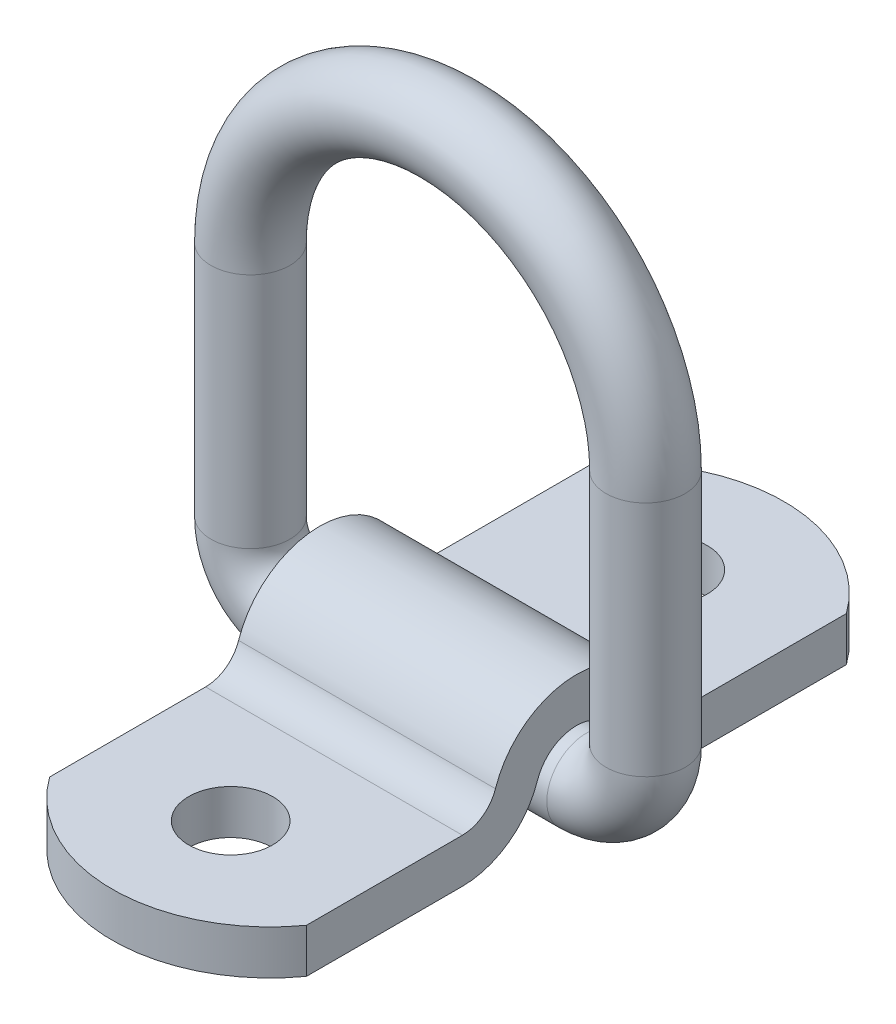
SolidWorks part; units mm, degrees
ref_plane "Front Plane" through (0, 0, 0) normal (0, 0, 1) x (1, 0, 0)
ref_plane "Top Plane" through (0, 0, 0) normal (0, 1, 0) x (1, 0, 0)
ref_plane "Right Plane" through (0, 0, 0) normal (1, 0, 0) x (0, 0, -1)
sketch "Sketch1" plane through (0, 0, 0) normal (0, 0, 1) x (1, 0, 0)
  line L1 (0, 0) -> (0, 42.8625) construction
  line L2 (-19.05, 23.8125) -> (-19.05, 4.7625) construction
  line L3 (-12.7, 23.8125) -> (-12.7, 3.175) construction
  line L4 (12.7, 23.8125) -> (12.7, 3.175) construction
  line L5 (19.05, 23.8125) -> (19.05, 4.7625) construction
  line L6 (12.7, 3.175) -> (-12.7, 3.175) construction
  line L7 (11.1125, -3.175) -> (-19.05, -3.175) construction
  line L8 (0, 3.175) -> (0, -3.175) construction
  line L10 (-15.875, 23.8125) -> (-15.875, 4.7625)
  line L11 (15.875, 23.8125) -> (15.875, 4.7625)
  line L12 (-11.1125, 0) -> (11.1125, 0)
  line L13 (-19.05, 4.7625) -> (-19.05, -3.175) construction
  arc A0 (19.05, 23.8125) -> (-19.05, 23.8125) centre (0, 23.8125) ccw construction
  arc A1 (12.7, 23.8125) -> (-12.7, 23.8125) centre (0, 23.8125) ccw construction
  circle A2 centre (0, 39.6875) radius 3.175 construction
  circle A3 centre (0, 0) radius 3.175 construction
  arc A4 (15.875, 23.8125) -> (-15.875, 23.8125) centre (0, 23.8125) ccw
  arc A5 (-11.1125, 0) -> (-15.875, 4.7625) centre (-11.1125, 4.7625) cw
  arc A6 (11.1125, 0) -> (15.875, 4.7625) centre (11.1125, 4.7625) ccw
  arc A7 (-11.1125, 3.175) -> (-12.7, 4.7625) centre (-11.1125, 4.7625) cw construction
  arc A8 (-11.1125, -3.175) -> (-19.05, 4.7625) centre (-11.1125, 4.7625) cw construction
  arc A9 (11.1125, -3.175) -> (19.05, 4.7625) centre (11.1125, 4.7625) ccw construction
  dimension "C" = 6.35
  dimension "D1" = 4.7625
  dimension "A" = 25.4
  dimension "B" = 46.0375
sketch "Sketch2" plane through (0, 0, 0) normal (1, 0, 0) x (0, 0, -1)
  circle A0 centre (0, 0) radius 3.175
sweep "Sweep1" add profiles "Sketch2" path "Sketch1"
sketch "Sketch3" plane through (0, 0, 0) normal (1, 0, 0) x (0, 0, -1)
  line L0 (-26.9875, -3.302) -> (26.9875, -3.302) construction
  line L1 (-26.9875, -3.302) -> (-26.9875, 0.254)
  line L2 (-26.9875, 0.254) -> (26.9875, 0.254) construction
  line L3 (0, 0) -> (0, -3.302) construction
  line L4 (26.9875, -3.302) -> (26.9875, 0.254)
  line L5 (-26.9875, -3.302) -> (-9.1581, -3.302)
  line L6 (-26.9875, 0.254) -> (-9.1581, 0.254)
  line L7 (-17.4625, -3.302) -> (-17.4625, 0.254) construction
  line L8 (26.9875, -3.302) -> (9.1581, -3.302)
  line L9 (26.9875, 0.254) -> (9.1581, 0.254)
  arc A0 (-9.1581, -3.302) -> (-3.133, 1.0427) centre (-9.1581, 3.048) ccw
  arc A1 (-3.133, 1.0427) -> (3.133, 1.0427) centre (0, 0) cw
  arc A2 (-9.1581, 0.254) -> (-6.5071, 2.1657) centre (-9.1581, 3.048) ccw
  arc A3 (-6.5071, 2.1657) -> (6.5071, 2.1657) centre (0, 0) cw
  arc A4 (9.1581, 0.254) -> (6.5071, 2.1657) centre (9.1581, 3.048) cw
  arc A5 (9.1581, -3.302) -> (3.133, 1.0427) centre (9.1581, 3.048) cw
  circle A6 centre (0, 0) radius 3.302 construction
  dimension "D1" = 34.925
  dimension "D4" = 6.604
  dimension "D5" = 6.35
  dimension "D2" = 3.556
  dimension "D3" = 53.975
extrude "Boss-Extrude1" add sketch "Sketch3" along normal mid plane 20.6375 separate body
sketch "Sketch4" plane through (0, -3.302, 0) normal (0, -1, 0) x (1, 0, 0)
  line L0 (-10.3187, 21.6911) -> (-10.3187, 26.9875)
  line L1 (-10.3187, 26.9875) -> (-10.3187, 27.2415)
  line L2 (-10.3187, 27.2415) -> (10.3187, 27.2415)
  line L3 (10.3187, 27.2415) -> (10.3187, 26.9875)
  line L4 (10.3187, 26.9875) -> (10.3187, 21.6911)
  line L5 (0, 14.2875) -> (0, 0) construction
  line L6 (10.3187, 26.9875) -> (-10.3187, 26.9875) construction
  line L7 (-10.3187, 0) -> (10.3188, 0) construction
  line L8 (10.3187, -26.9875) -> (10.3187, -21.6911)
  line L9 (10.3187, -27.2415) -> (10.3187, -26.9875)
  line L10 (-10.3187, -27.2415) -> (10.3187, -27.2415)
  line L11 (-10.3187, -26.9875) -> (-10.3187, -27.2415)
  line L12 (-10.3187, -21.6911) -> (-10.3187, -26.9875)
  arc A0 (10.3187, 21.6911) -> (-10.3187, 21.6911) centre (0, 14.2875) ccw
  circle A1 centre (0, 17.4625) radius 3.3734
  circle A2 centre (0, -17.4625) radius 3.3734
  arc A3 (10.3187, -21.6911) -> (-10.3187, -21.6911) centre (0, -14.2875) cw
  dimension "D1" = 12.7
  dimension "D3" = 6.7469
  dimension "D4" = 5.2964
  dimension "D2" = 0.254
extrude "Cut-Extrude1" cut sketch "Sketch4" against normal through all
